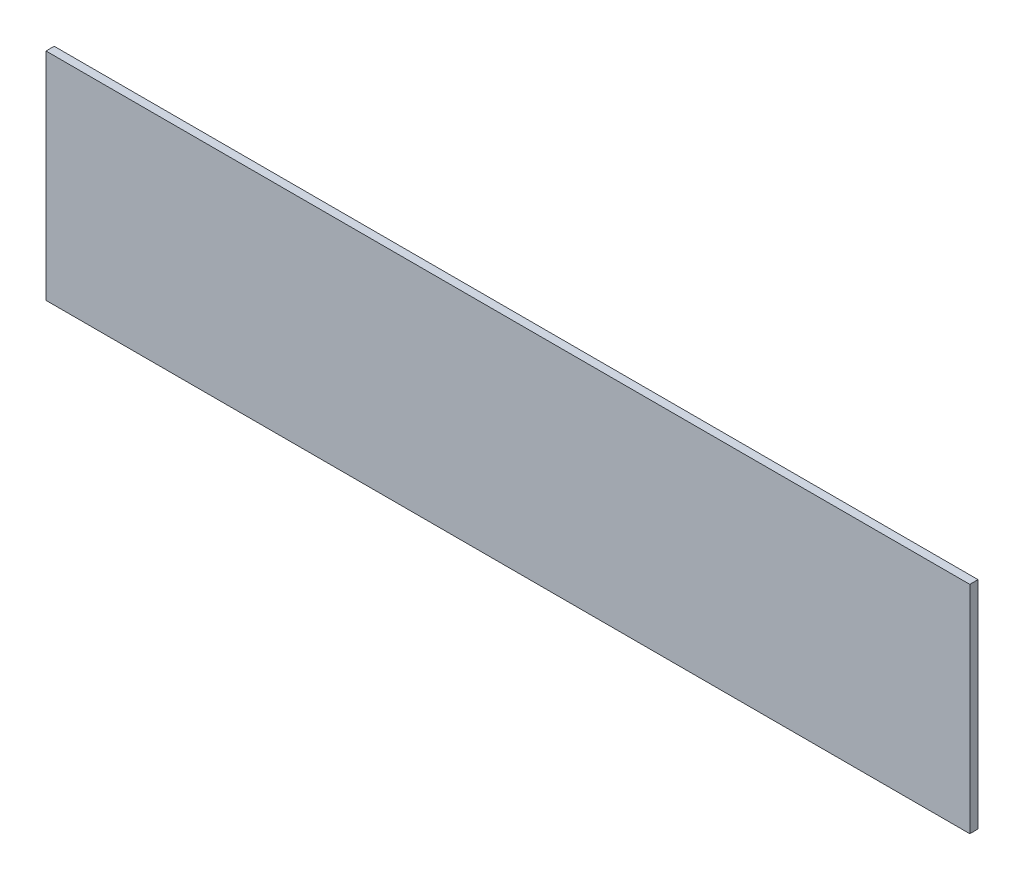
SolidWorks part; units mm, degrees
material "Custom Plastic"
ref_plane "X-Y Datum" through (0, 0, 0) normal (0, 0, 1) x (1, 0, 0)
ref_plane "X-Z Datum" through (0, 0, 0) normal (0, 1, 0) x (1, 0, 0)
ref_plane "Y-Z Datum" through (0, 0, 0) normal (1, 0, 0) x (0, 0, -1)
sketch "Sketch1" plane through (0, 0, 0) normal (0, 0, 1) x (1, 0, 0)
  line L1 (-178.775, 41.8) -> (178.775, 41.8)
  line L2 (-178.775, 41.8) -> (-178.775, -41.8)
  line L3 (-178.775, -41.8) -> (178.775, -41.8)
  line L4 (178.775, 41.8) -> (178.775, -41.8)
  line L5 (-178.775, 41.8) -> (178.775, -41.8) construction
  line L6 (-178.775, -41.8) -> (178.775, 41.8) construction
  point P0 (0, 0)
  dimension "D1" = 357.55
  dimension "D2" = 83.6
extrude "Boss-Extrude1" add sketch "Sketch1" along normal blind 3.175
